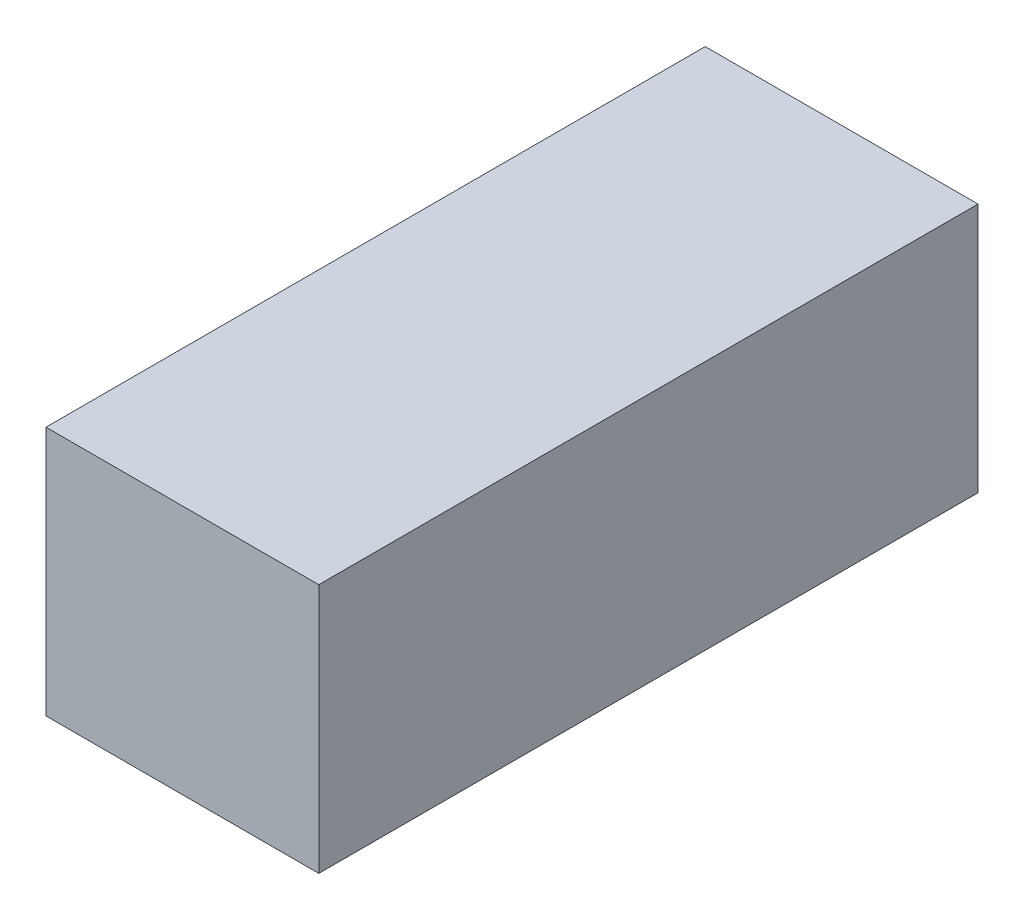
SolidWorks part; units mm, degrees
ref_plane "Plan de face" through (0, 0, 0) normal (0, 0, 1) x (1, 0, 0)
ref_plane "Plan de dessus" through (0, 0, 0) normal (0, 1, 0) x (1, 0, 0)
ref_plane "Plan de droite" through (0, 0, 0) normal (1, 0, 0) x (0, 0, -1)
sketch "Esquisse1" plane through (0, 0, 0) normal (0, 0, 1) x (1, 0, 0)
  line L1 (-6, -5.5) -> (6, -5.5)
  line L2 (-6, -5.5) -> (-6, 5.5)
  line L3 (-6, 5.5) -> (6, 5.5)
  line L4 (6, -5.5) -> (6, 5.5)
  line L5 (-6, -5.5) -> (6, 5.5) construction
  line L6 (-6, 5.5) -> (6, -5.5) construction
  point P0 (0, 0)
  dimension "D1" = 12
  dimension "D2" = 11
extrude "Boss.-Extru.1" add sketch "Esquisse1" along normal blind 29
